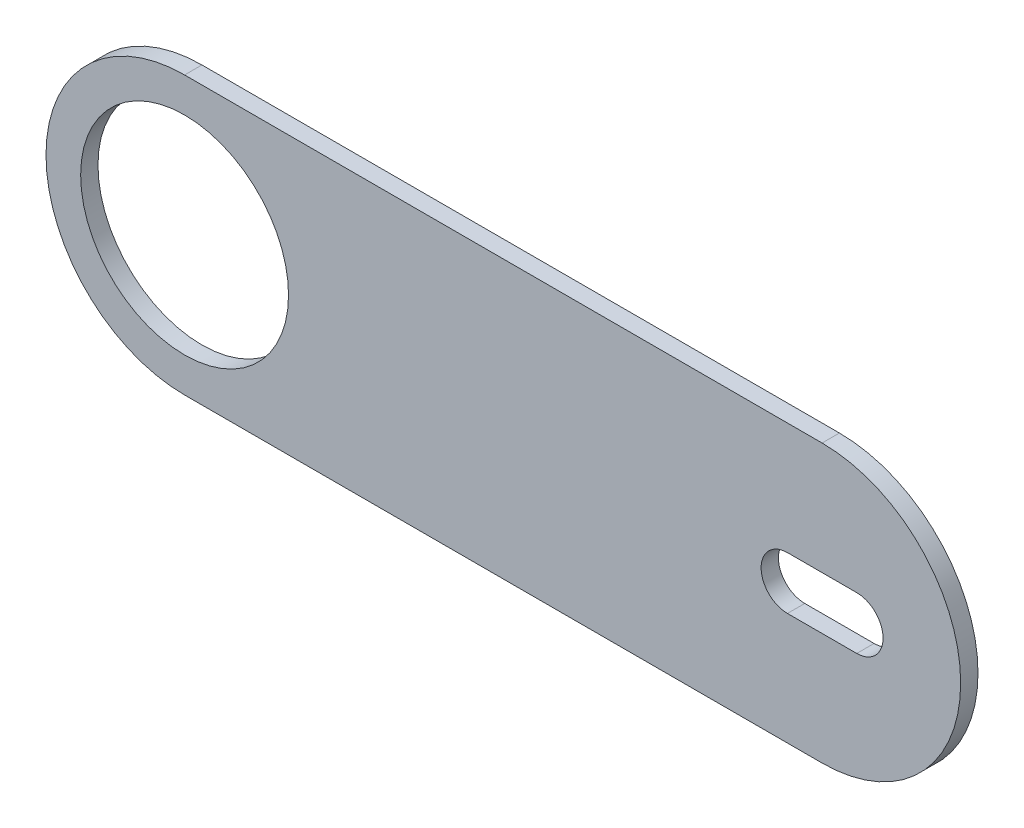
SolidWorks part; units mm, degrees
ref_plane "Front Plane" through (0, 0, 0) normal (0, 0, 1) x (1, 0, 0)
ref_plane "Top Plane" through (0, 0, 0) normal (0, 1, 0) x (1, 0, 0)
ref_plane "Right Plane" through (0, 0, 0) normal (1, 0, 0) x (0, 0, -1)
sketch "Sketch1" plane through (0, 0, 0) normal (0, 0, 1) x (1, 0, 0)
  line L0 (-29.21, 0) -> (29.21, 0) construction
  line L1 (-29.21, 12.7) -> (29.21, 12.7)
  line L2 (-29.21, -12.7) -> (29.21, -12.7)
  line L3 (32.385, 0) -> (26.035, 0) construction
  line L4 (32.385, -2.413) -> (26.035, -2.413)
  line L5 (32.385, 2.413) -> (26.035, 2.413)
  arc A0 (-29.21, 12.7) -> (-29.21, -12.7) centre (-29.21, 0) ccw
  arc A1 (29.21, -12.7) -> (29.21, 12.7) centre (29.21, 0) ccw
  arc A2 (32.385, -2.413) -> (32.385, 2.413) centre (32.385, 0) ccw
  arc A3 (26.035, 2.413) -> (26.035, -2.413) centre (26.035, 0) ccw
  circle A4 centre (-29.21, 0) radius 9.525
  point P2 (0, 0)
  point P10 (29.21, 0)
extrude "Boss-Extrude1" add sketch "Sketch1" along normal blind 1.5875
